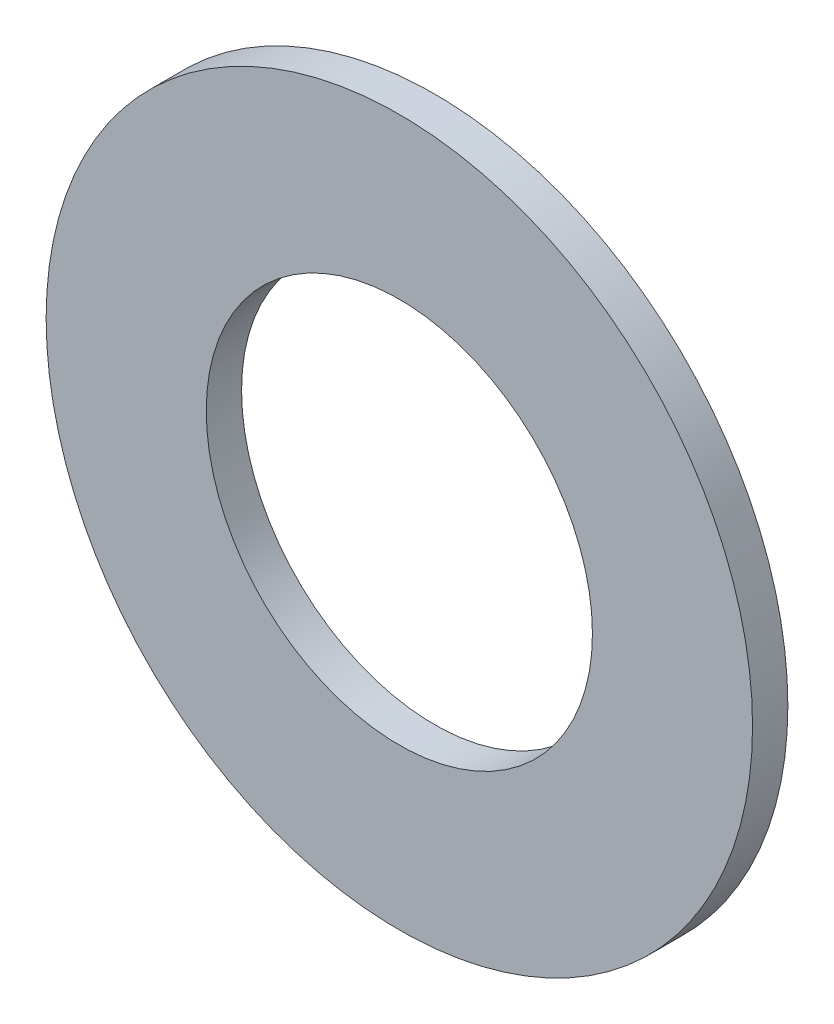
SolidWorks part; units mm, degrees
ref_plane "Front Plane" through (0, 0, 0) normal (0, 0, 1) x (1, 0, 0)
ref_plane "Top Plane" through (0, 0, 0) normal (0, 1, 0) x (1, 0, 0)
ref_plane "Right Plane" through (0, 0, 0) normal (1, 0, 0) x (0, 0, -1)
sketch "Sketch1" plane through (0, 0, 0) normal (0, 0, 1) x (1, 0, 0)
  circle A0 centre (0, 0) radius 7.5
  circle A1 centre (0, 0) radius 4.1
  dimension "D1" = 8.2
  dimension "D2" = 15
extrude "Boss-Extrude1" add sketch "Sketch1" along normal blind 0.75
